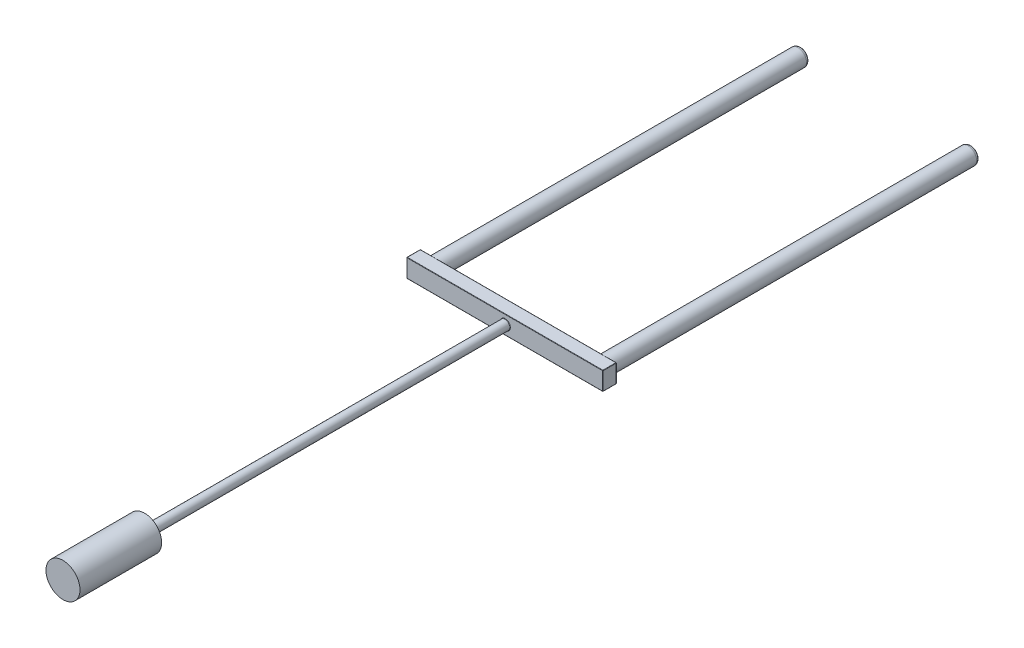
SolidWorks part; units mm, degrees
ref_plane "Front Plane" through (0, 0, 0) normal (0, 0, 1) x (1, 0, 0)
ref_plane "Top Plane" through (0, 0, 0) normal (0, 1, 0) x (1, 0, 0)
ref_plane "Right Plane" through (0, 0, 0) normal (1, 0, 0) x (0, 0, -1)
sketch "Sketch1" plane through (0, 0, 0) normal (0, 0, 1) x (1, 0, 0)
  circle A0 centre (0, 0) radius 7
  point P0 (0, 0)
  dimension "D1" = 14
extrude "Boss-Extrude1" add sketch "Sketch1" along normal blind 500 and the other way blind 100
ref_plane "Plane2" through (0, 0, -650) normal (0, 0, 1) x (1, 0, 0)
sketch "Sketch4" plane through (0, 0, -650) normal (0, 0, 1) x (1, 0, 0)
  circle A0 centre (-125, 0) radius 12.5
  circle A1 centre (125, 0) radius 12.5
  dimension "D1" = 25
  dimension "D2" = 25
  dimension "D3" = 250
  dimension "D4" = 125
extrude "Boss-Extrude2" add sketch "Sketch4" along normal blind 550 separate body
sketch "Sketch5" plane through (0, 0, -100) normal (0, 0, -1) x (-1, 0, 0)
  line L1 (-143.3177, 13.245) -> (144.9026, 13.245)
  line L2 (-143.3177, 13.245) -> (-143.3177, -13.6978)
  line L3 (-143.3177, -13.6978) -> (144.9026, -13.6978)
  line L4 (144.9026, 13.245) -> (144.9026, -13.6978)
extrude "Boss-Extrude3" add sketch "Sketch5" along normal blind 10 and the other way blind 10
fillet "Fillet4" radius 0.5 1 edges at (-7, 0, -90)
fillet "Fillet8" radius 0.5 12 edges at (-144.9026, -0.2264, -110) (-0.7924, 13.245, -90) (143.3177, -0.2264, -110) (-0.7924, 13.245, -110) (143.3177, 13.245, -100) (143.3177, -0.2264, -90) (-0.7924, -13.6978, -90) (143.3177, -13.6978, -100) (-0.7924, -13.6978, -110) (-144.9026, -13.6978, -100) (-144.9026, -0.2264, -90) (-144.9026, 13.245, -100)
fillet "Fillet9" radius 5 2 edges at (-112.5, 0, -650) (137.5, 0, -650)
sketch "Sketch6" plane through (0, 0, 500) normal (0, 0, 1) x (1, 0, 0)
  circle A0 centre (0, 0) radius 25
  dimension "D1" = 50
extrude "Boss-Extrude4" add sketch "Sketch6" along normal blind 60 and the other way blind 60
